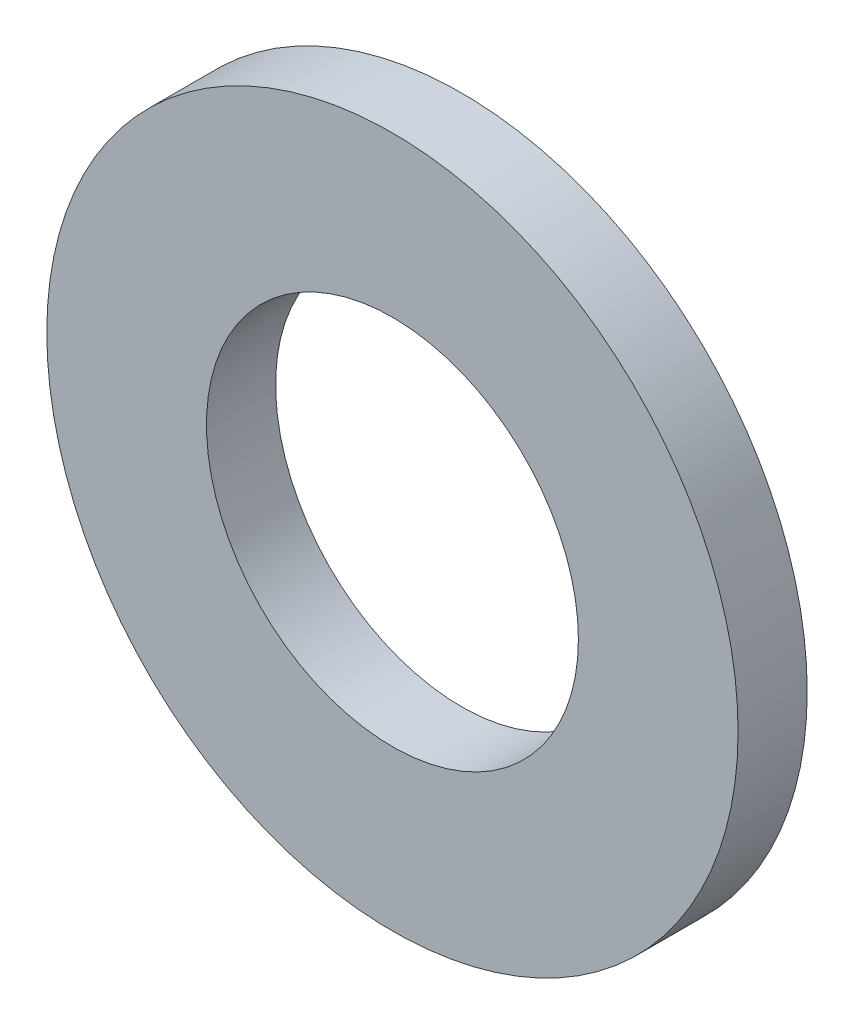
SolidWorks part; units mm, degrees
ref_plane "Спереди(Плоскость XY)" through (0, 0, 0) normal (0, 0, 1) x (1, 0, 0)
ref_plane "Сверху(Плоскость XZ)" through (0, 0, 0) normal (0, 1, 0) x (1, 0, 0)
ref_plane "Справа(Плоскость ZY)" through (0, 0, 0) normal (1, 0, 0) x (0, 0, -1)
sketch "Эскиз1" plane through (0, 0, 0) normal (0, 0, 1) x (1, 0, 0)
  circle A0 centre (0, 0) radius 1.345
  circle A1 centre (0, 0) radius 2.5
  dimension "D1" = 2.69
  dimension "D2" = 5
extrude "Бобышка-Вытянуть1" add sketch "Эскиз1" against normal blind 0.5 contours A0 | A1
